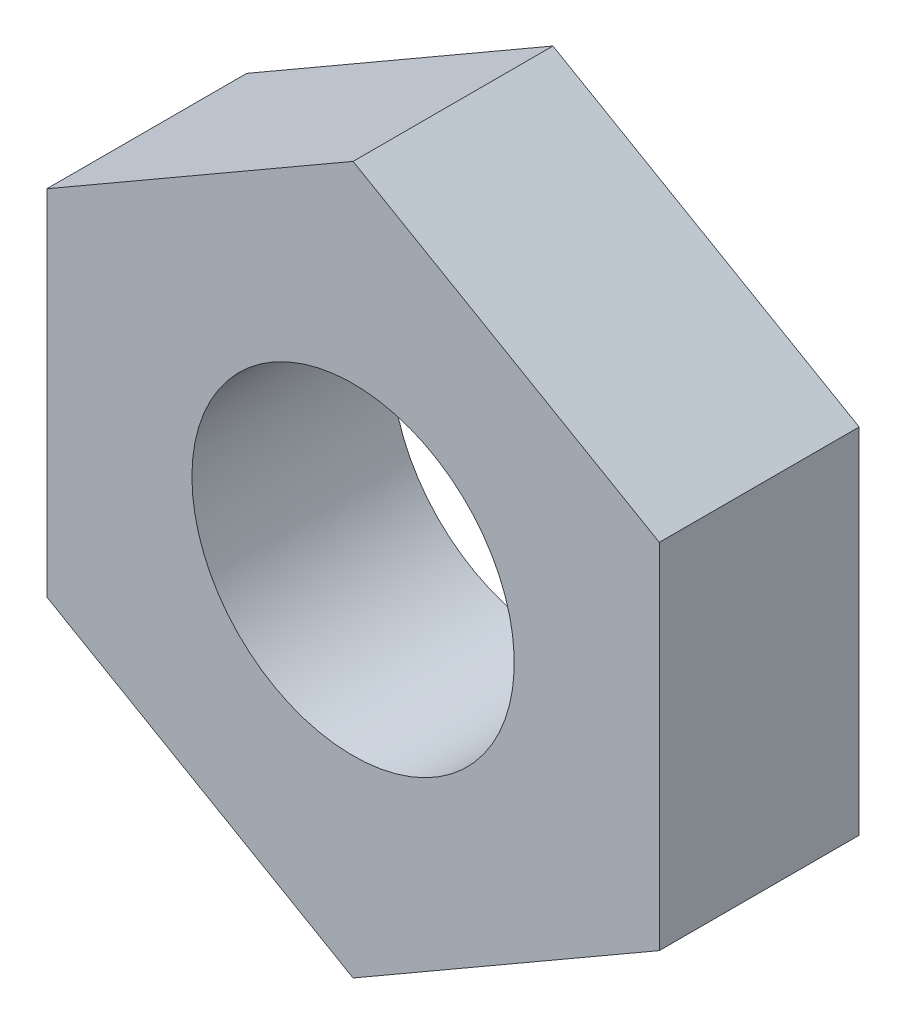
SolidWorks part; units mm, degrees
ref_plane "Front Plane" through (0, 0, 0) normal (0, 0, 1) x (1, 0, 0)
ref_plane "Top Plane" through (0, 0, 0) normal (0, 1, 0) x (1, 0, 0)
ref_plane "Right Plane" through (0, 0, 0) normal (1, 0, 0) x (0, 0, -1)
sketch "Sketch1" plane through (0, 0, 0) normal (0, 0, 1) x (1, 0, 0)
  line L1 (20, -25.4848) -> (24.75, -22.7424)
  line L2 (24.75, -22.7424) -> (24.75, -17.2576)
  line L3 (24.75, -17.2576) -> (20, -14.5152)
  line L4 (20, -14.5152) -> (15.25, -17.2576)
  line L5 (15.25, -17.2576) -> (15.25, -22.7424)
  line L6 (15.25, -22.7424) -> (20, -25.4848)
  circle A0 centre (20, -20) radius 4.75 construction
  circle A1 centre (20, -20) radius 2.5
extrude "Boss-Extrude1" add sketch "Sketch1" along normal blind 3.1
